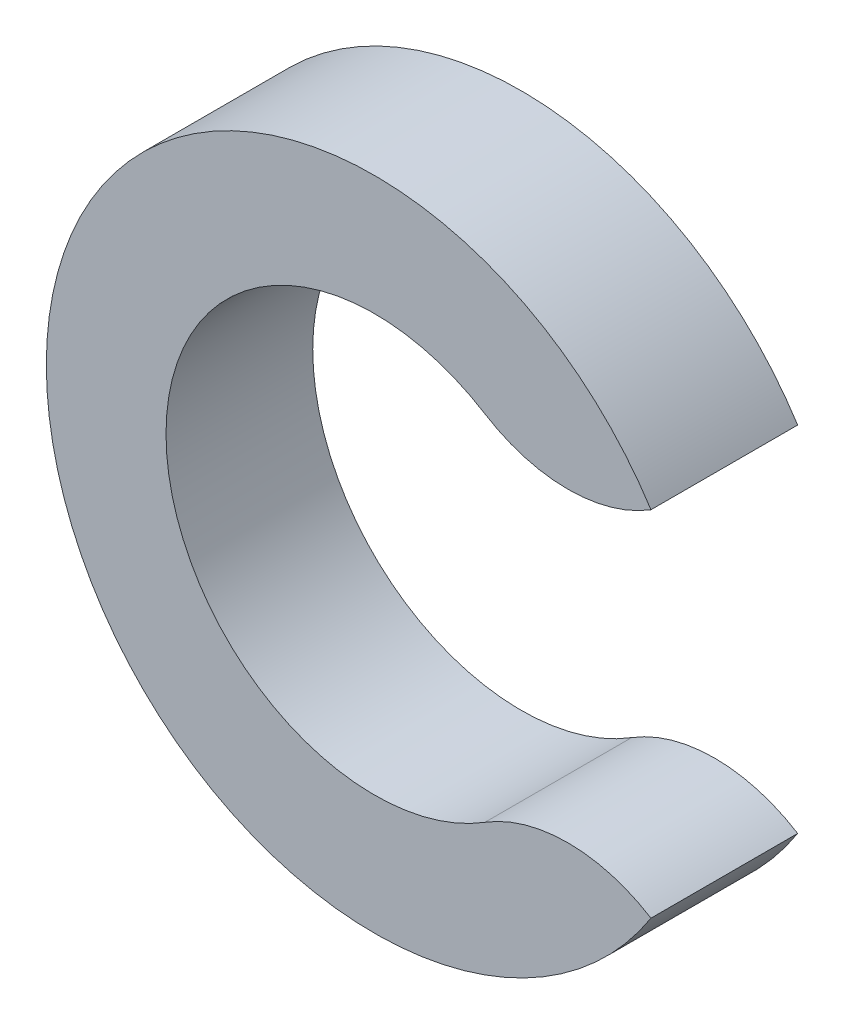
SolidWorks part; units mm, degrees
ref_plane "Front Plane" through (0, 0, 0) normal (0, 0, 1) x (1, 0, 0)
ref_plane "Top Plane" through (0, 0, 0) normal (0, 1, 0) x (1, 0, 0)
ref_plane "Right Plane" through (0, 0, 0) normal (1, 0, 0) x (0, 0, -1)
sketch "Sketch1" plane through (0, 0, 0) normal (0, 0, 1) x (1, 0, 0)
  line L0 (1.4299, 2.2903) -> (1.4299, -2.2903) construction
  circle A0 centre (0, 0) radius 2.7 construction
  arc A1 (1.4299, 2.2903) -> (3.5801, 2.2903) centre (2.505, 4.0122) ccw
  circle A2 centre (0, 0) radius 4.25
  arc A3 (1.4299, -2.2903) -> (3.5801, -2.2903) centre (2.505, -4.0122) cw
  arc A4 (1.4299, -2.2903) -> (1.4299, 2.2903) centre (0, 0) cw
  point P6 (1.4299, 0)
  dimension "D1" = 5.4
  dimension "D2" = 8.5
extrude "Boss-Extrude1" add sketch "Sketch1" along normal blind 1.9 contours A3 A4 A1 A2
